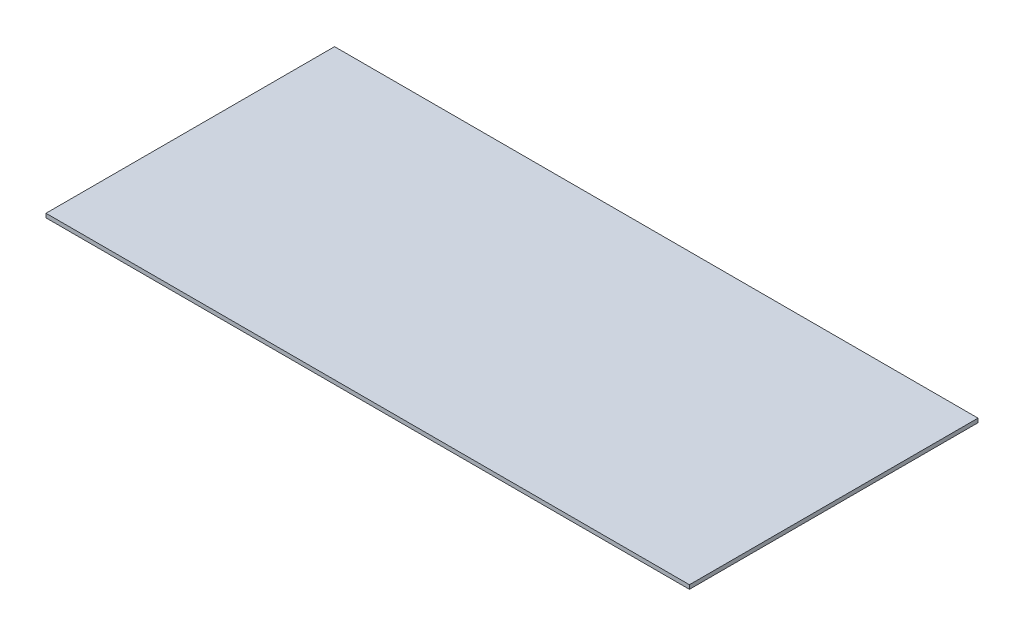
SolidWorks part; units mm, degrees
ref_plane "Front Plane" through (0, 0, 0) normal (0, 0, 1) x (1, 0, 0)
ref_plane "Top Plane" through (0, 0, 0) normal (0, 1, 0) x (1, 0, 0)
ref_plane "Right Plane" through (0, 0, 0) normal (1, 0, 0) x (0, 0, -1)
sketch "Sketch1" plane through (0, 0, 0) normal (0, 1, 0) x (1, 0, 0)
  line L1 (0, 0) -> (508, 0)
  line L2 (0, 0) -> (0, 227.838)
  line L3 (0, 227.838) -> (508, 227.838)
  line L4 (508, 0) -> (508, 227.838)
  dimension "D1" = 508
  dimension "D2" = 227.838
extrude "Boss-Extrude1" add sketch "Sketch1" along normal blind 3.175
